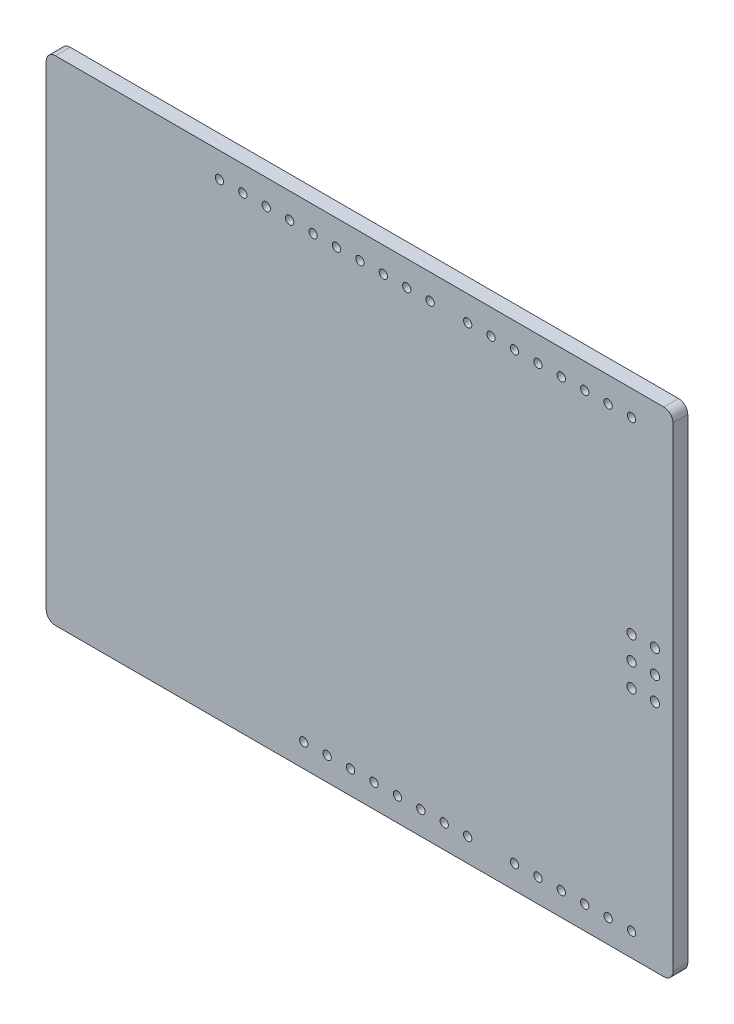
SolidWorks part; units mm, degrees
ref_plane "Ebene vorne" through (0, 0, 0) normal (0, 0, 1) x (1, 0, 0)
ref_plane "Ebene oben" through (0, 0, 0) normal (0, 1, 0) x (1, 0, 0)
ref_plane "Ebene rechts" through (0, 0, 0) normal (1, 0, 0) x (0, 0, -1)
sketch "Skizze1" plane through (0, 0, 0) normal (0, 0, 1) x (1, 0, 0)
  line L7 (0, 53.53) -> (68, 53.53)
  line L8 (0, 53.53) -> (0, 0)
  line L9 (0, 0) -> (68, 0)
  line L10 (68, 53.53) -> (68, 0)
  dimension "D1" = 68
  dimension "D2" = 53.53
extrude "Aufsatz-Linear austragen1" add sketch "Skizze1" along normal blind 1.6
sketch "Skizze2" plane through (0, 0, 1.6) normal (0, 0, 1) x (1, 0, 0)
  line L0 (0, 50.8) -> (68, 50.8) construction
  line L1 (0, 53.53) -> (0, 0) construction
  line L2 (68, 0) -> (68, 53.53) construction
  line L3 (0, 2.54) -> (68, 2.54) construction
  line L4 (0, 0) -> (68, 0) construction
  line L5 (41.65, 50.8) -> (41.65, 41.4322) construction
  line L6 (45.72, 2.54) -> (45.72, 8.7942) construction
  line L7 (63.5, 50.8) -> (63.5, 45.8466) construction
  line L8 (63.5, 2.54) -> (63.5, 6.8837) construction
  line L9 (63.5, 25.35) -> (66.04, 25.35) construction
  line L10 (66.04, 25.35) -> (66.04, 30.43) construction
  line L11 (66.04, 30.43) -> (63.5, 30.43) construction
  line L12 (63.5, 30.43) -> (63.5, 25.35) construction
  line L13 (64.77, 30.43) -> (64.77, 25.35) construction
  line L14 (64.77, 27.89) -> (60.5423, 27.89) construction
  circle A0 centre (45.72, 2.54) radius 0.45
  circle A1 centre (63.5, 2.54) radius 0.45
  circle A2 centre (63.5, 50.8) radius 0.45
  circle A3 centre (41.65, 50.8) radius 0.45
  circle A4 centre (43.18, 2.54) radius 0.45
  circle A5 centre (40.64, 2.54) radius 0.45
  circle A6 centre (38.1, 2.54) radius 0.45
  circle A7 centre (35.56, 2.54) radius 0.45
  circle A8 centre (33.02, 2.54) radius 0.45
  circle A9 centre (60.96, 2.54) radius 0.45
  circle A10 centre (58.42, 2.54) radius 0.45
  circle A11 centre (55.88, 2.54) radius 0.45
  circle A12 centre (53.34, 2.54) radius 0.45
  circle A13 centre (50.8, 2.54) radius 0.45
  circle A14 centre (30.48, 2.54) radius 0.45
  circle A15 centre (27.94, 2.54) radius 0.45
  circle A16 centre (39.11, 50.8) radius 0.45
  circle A17 centre (36.57, 50.8) radius 0.45
  circle A18 centre (34.03, 50.8) radius 0.45
  circle A19 centre (31.49, 50.8) radius 0.45
  circle A20 centre (28.95, 50.8) radius 0.45
  circle A21 centre (26.41, 50.8) radius 0.45
  circle A22 centre (23.87, 50.8) radius 0.45
  circle A23 centre (21.33, 50.8) radius 0.45
  circle A24 centre (18.79, 50.8) radius 0.45
  circle A25 centre (60.96, 50.8) radius 0.45
  circle A26 centre (58.42, 50.8) radius 0.45
  circle A27 centre (55.88, 50.8) radius 0.45
  circle A28 centre (53.34, 50.8) radius 0.45
  circle A29 centre (50.8, 50.8) radius 0.45
  circle A30 centre (48.26, 50.8) radius 0.45
  circle A31 centre (45.72, 50.8) radius 0.45
  circle A32 centre (63.5, 25.35) radius 0.5
  circle A33 centre (63.5, 27.89) radius 0.5
  circle A34 centre (63.5, 30.43) radius 0.5
  circle A35 centre (66.04, 30.43) radius 0.5
  circle A37 centre (66.04, 25.35) radius 0.5
  circle A38 centre (66.04, 27.89) radius 0.5
  point P90 (63.5, 27.89)
  point P91 (66.04, 27.89)
  point P96 (0, 0)
  dimension "D3" = 0.9
  dimension "D4" = 0.9
  dimension "D5" = 0.9
  dimension "D6" = 0.9
  dimension "D15" = 1
  dimension "D16" = 1
  dimension "D17" = 1
  dimension "D18" = 1
  dimension "D19" = 1
  dimension "D20" = 1
  dimension "D1" = 2.54
  dimension "D2" = 50.8
  dimension "D7" = 45.72
  dimension "D8" = 41.65
  dimension "D9" = 63.5
  dimension "D10" = 63.5
  dimension "D21" = 2.54
  dimension "D22" = 5.08
  dimension "D23" = 22.81
  dimension "D11" = 8
  dimension "D12" = 6
  dimension "D13" = 10
  dimension "D14" = 8
extrude "Schnitt-Linear austragen1" cut sketch "Skizze2" against normal blind 1.6
fillet "Verrundung1" radius 1 4 edges at (0, 53.53, 0.8) (68, 53.53, 0.8) (68, 0, 0.8) (0, 0, 0.8)
